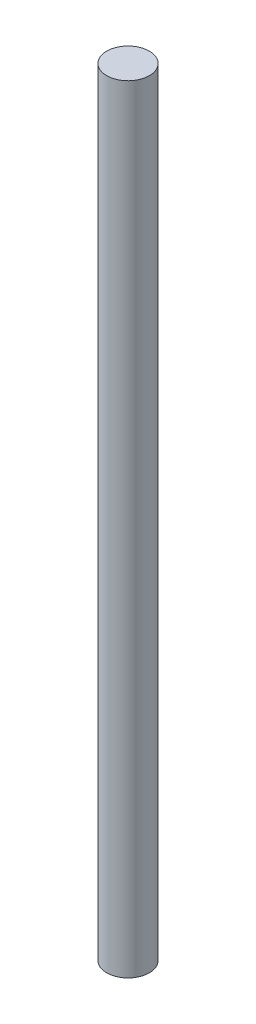
SolidWorks part; units mm, degrees
ref_plane "前视基准面" through (0, 0, 0) normal (0, 0, 1) x (1, 0, 0)
ref_plane "上视基准面" through (0, 0, 0) normal (0, 1, 0) x (1, 0, 0)
ref_plane "右视基准面" through (0, 0, 0) normal (1, 0, 0) x (0, 0, -1)
other "Configuration Table"
sketch "草图1" plane through (0, 0, 0) normal (0, 1, 0) x (1, 0, 0)
  circle A0 centre (0, 0) radius 2.5
  dimension "D1" = 5
extrude "凸台-拉伸1" add sketch "草图1" along normal blind 173.2
cosmetic thread "装饰螺纹线2" parameters "D1"=6.6, "D2"=4
cosmetic thread "装饰螺纹线3" parameters "D1"=5, "D2"=4
ref_plane "基准面2" through (0, 163.6, 0) normal (0, 1, 0) x (1, 0, 0)
sketch "草图3" plane through (0, 163.6, 0) normal (0, 1, 0) x (1, 0, 0)
  circle A0 centre (0, 0) radius 77
  dimension "D1" = 154
extrude "凸台-拉伸4" add sketch "草图3" against normal blind 4
ref_plane "基准面4" through (0, 9.6, 0) normal (0, -1, 0) x (-1, 0, 0)
sketch "草图5" plane through (0, 9.6, 0) normal (0, -1, 0) x (-1, 0, 0)
  circle A0 centre (0, 0) radius 77
  dimension "D1" = 154
ref_plane "基准面7" through (0, 159.6, 0) normal (0, -1, 0) x (-1, 0, 0)
sketch "草图8" plane through (0, 159.6, 0) normal (0, -1, 0) x (-1, 0, 0)
  circle A0 centre (0, 0) radius 15
  dimension "D1" = 30
extrude "凸台-拉伸7" add sketch "草图8" along normal blind 3
ref_plane "基准面8" through (0, 163.6, 0) normal (0, 1, 0) x (1, 0, 0)
sketch "草图9" plane through (0, 163.6, 0) normal (0, 1, 0) x (1, 0, 0)
  line L0 (0, 77) -> (0, -35.3651) construction
  circle A0 centre (0, 0) radius 77 construction
  circle A1 centre (0, 45) radius 5
  dimension "D1" = 10
  dimension "D2" = 45
extrude "切除-拉伸2" cut sketch "草图9" against normal up to next
cosmetic thread "装饰螺纹线1" parameters "D2"=11
pattern_circular "阵列(圆周)1" count 3 over 360 about axis through (0, 0, 0) along (0, 1, 0) of "切除-拉伸2"
ref_plane "基准面11" through (0, 82, 0) normal (0, 1, 0) x (1, 0, 0)
sketch "草图11" plane through (0, 82, 0) normal (0, 1, 0) x (1, 0, 0)
  circle A0 centre (0, 0) radius 2.5
extrude "切除-拉伸4" cut sketch "草图11" against normal through all
ref_plane "基准面12" through (0, 153.6, 0) normal (0, -1, 0) x (-1, 0, 0)
sketch "草图12" plane through (0, 153.6, 0) normal (0, -1, 0) x (-1, 0, 0)
  circle A0 centre (0, 0) radius 2.5
extrude "凸台-拉伸8" add sketch "草图12" along normal blind 6.6
sketch "草图13" plane through (0, 163.6, 0) normal (0, 1, 0) x (1, 0, 0)
  circle A0 centre (0, 0) radius 15
  circle A1 centre (0, 0) radius 77
  dimension "D1" = 30
extrude "切除-拉伸6" cut sketch "草图13" against normal up to next
sketch "草图14" plane through (0, 163.6, 0) normal (0, 1, 0) x (1, 0, 0)
  circle A0 centre (0, 0) radius 15
extrude "切除-拉伸7" cut sketch "草图14" against normal blind 10
sketch "草图15" plane through (0, 153.6, 0) normal (0, -1, 0) x (-1, 0, 0)
  circle A0 centre (0, 0) radius 2.5
extrude "凸台-拉伸9" add sketch "草图15" against normal blind 10
